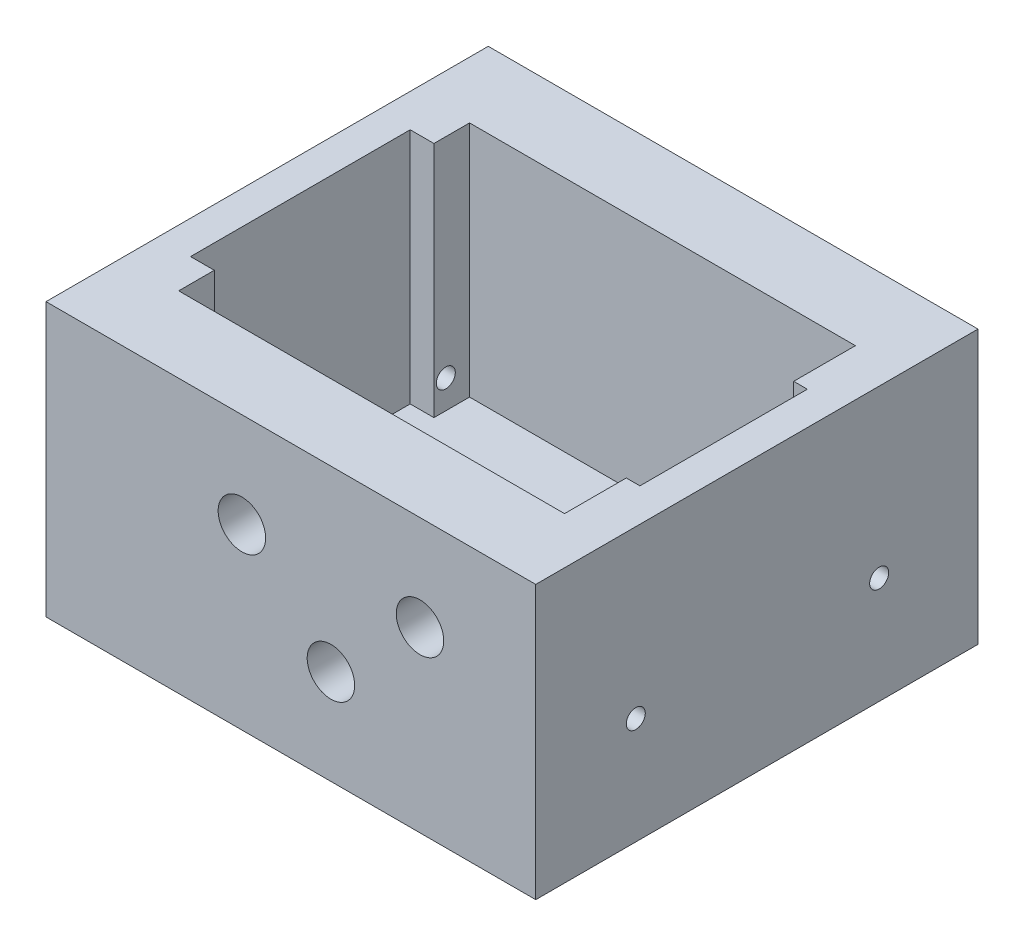
SolidWorks part; units mm, degrees
ref_plane "Front Plane" through (0, 0, 0) normal (0, 0, 1) x (1, 0, 0)
ref_plane "Top Plane" through (0, 0, 0) normal (0, 1, 0) x (1, 0, 0)
ref_plane "Right Plane" through (0, 0, 0) normal (1, 0, 0) x (0, 0, -1)
sketch "Sketch1" plane through (0, 0, 0) normal (0, 1, 0) x (1, 0, 0)
  line L1 (0, 0) -> (41.25, 0)
  line L2 (0, 0) -> (0, 37.25)
  line L3 (0, 37.25) -> (41.25, 37.25)
  line L4 (41.25, 0) -> (41.25, 37.25)
  dimension "D1" = 37.25
  dimension "D2" = 41.25
extrude "Boss-Extrude1" add sketch "Sketch1" along normal blind 23
sketch "Sketch2" plane through (0, 23, 0) normal (0, 1, 0) x (1, 0, 0)
  line L0 (22.5, 34.3711) -> (22.5, -3.2198) construction
  line L1 (0, 37.25) -> (0, 0) construction
  line L2 (37.3, 30.875) -> (4.8, 30.875)
  line L3 (4.8, 30.875) -> (4.8, 27.875)
  line L4 (4.8, 27.875) -> (2.8, 27.875)
  line L5 (2.8, 27.875) -> (2.8, 9.375)
  line L6 (2.8, 9.375) -> (4.8, 9.375)
  line L7 (4.8, 9.375) -> (4.8, 6.375)
  line L8 (4.8, 6.375) -> (37.3, 6.375)
  line L9 (37.3, 6.375) -> (37.3, 11.575)
  line L10 (37.3, 11.575) -> (38.45, 11.575)
  line L11 (38.45, 11.575) -> (38.45, 25.675)
  line L12 (38.45, 25.675) -> (37.3, 25.675)
  line L13 (37.3, 25.675) -> (37.3, 30.875)
  line L15 (0, 0) -> (41.25, 0) construction
  line L16 (41.25, 0) -> (41.25, 37.25) construction
  dimension "D1" = 22.5
  dimension "D2" = 1.15
  dimension "D3" = 32.5
  dimension "D4" = 3
  dimension "D5" = 18.5
  dimension "D6" = 5.2
  dimension "D7" = 14.1
  dimension "D8" = 2.8
  dimension "D9" = 2
  dimension "D10" = 2
  dimension "D11" = 6.375
  dimension "D12" = 3
extrude "Cut-Extrude1" cut sketch "Sketch2" against normal blind 20
sketch "Sketch3" plane through (37.3, 0, 0) normal (-1, 0, 0) x (0, 0, 1)
  line L3 (-11.575, 3) -> (-11.575, 23) construction
  line L4 (-11.575, 3) -> (-25.675, 3) construction
  line L5 (-25.675, 3) -> (-25.675, 23) construction
  line L6 (-11.575, 3) -> (-11.575, 23)
  line L7 (-11.575, 3) -> (-25.675, 3)
  line L8 (-25.675, 3) -> (-25.675, 23)
  circle A2 centre (-28.925, 9) radius 0.8
  circle A3 centre (-8.425, 9) radius 0.8
  dimension "D5" = 1.6
  dimension "D6" = 6
  dimension "D7" = 20.5
  dimension "D8" = 3.25
extrude "Cut-Extrude2" cut sketch "Sketch3" against normal up to surface (3.95 mm away) contours A2 | A3 up to face at (41.25, 11.5, -18.625)
sketch "Sketch4" plane through (4.8, 0, 0) normal (1, 0, 0) x (0, 0, -1)
  line L3 (27.875, 3) -> (27.875, 23) construction
  line L4 (27.875, 3) -> (9.375, 3) construction
  line L5 (9.375, 3) -> (9.375, 23) construction
  line L6 (27.875, 3) -> (27.875, 23)
  line L7 (27.875, 3) -> (9.375, 3)
  line L8 (9.375, 3) -> (9.375, 23)
  circle A2 centre (8.375, 5.4) radius 0.8
  circle A3 centre (28.875, 5.4) radius 0.8
  dimension "D5" = 1.6
  dimension "D6" = 20.5
  dimension "D7" = 1
  dimension "D8" = 2.4
extrude "Cut-Extrude3" cut sketch "Sketch4" against normal up to surface (4.8 mm away) contours A3 | A2 up to face at (0, 11.5, -18.625)
sketch "Sketch5" plane through (0, 0, 0) normal (0, 0, 1) x (1, 0, 0)
  line L0 (0, 23) -> (0, 0) construction
  line L1 (0, 0) -> (41.25, 0) construction
  circle A0 centre (16.5, 15) radius 2
  circle A1 centre (31.5, 15) radius 2
  circle A2 centre (24, 8) radius 2
  dimension "D1" = 4
  dimension "D2" = 15
  dimension "D3" = 16.5
  dimension "D4" = 15
  dimension "D5" = 7
  dimension "D6" = 7.5
extrude "Cut-Extrude4" cut sketch "Sketch5" against normal blind 5.5
ref_plane "Plane1" through (0, 0, -18.625) normal (0, 0, 1) x (1, 0, 0)
mirror "Mirror1" about plane through (0, 0, -18.625) normal (0, 0, 1) of "Cut-Extrude4"
